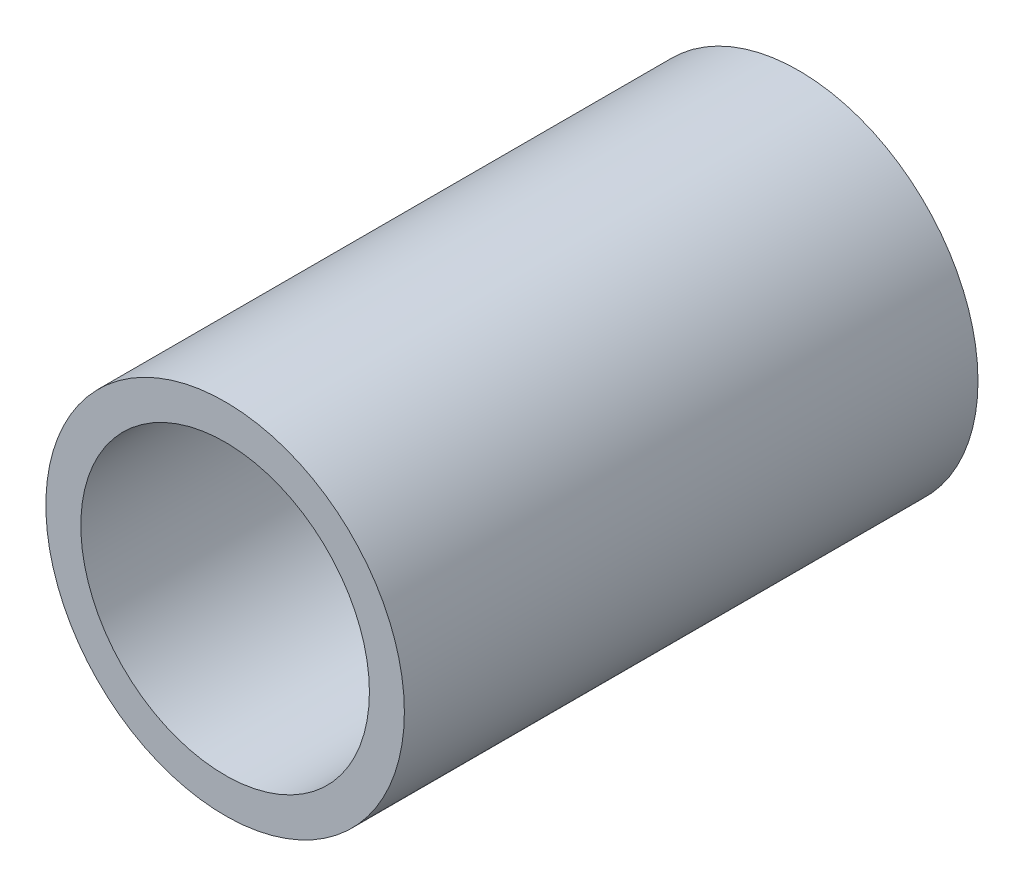
SolidWorks part; units mm, degrees
ref_plane "Front Plane" through (0, 0, 0) normal (0, 0, 1) x (1, 0, 0)
ref_plane "Top Plane" through (0, 0, 0) normal (0, 1, 0) x (1, 0, 0)
ref_plane "Right Plane" through (0, 0, 0) normal (1, 0, 0) x (0, 0, -1)
sketch "Sketch1" plane through (0, 0, 0) normal (0, 0, 1) x (1, 0, 0)
  circle A0 centre (0, 0) radius 4.025
  circle A1 centre (0, 0) radius 5
  dimension "D1" = 8.05
  dimension "D2" = 10
extrude "Boss-Extrude1" add sketch "Sketch1" along normal blind 16
